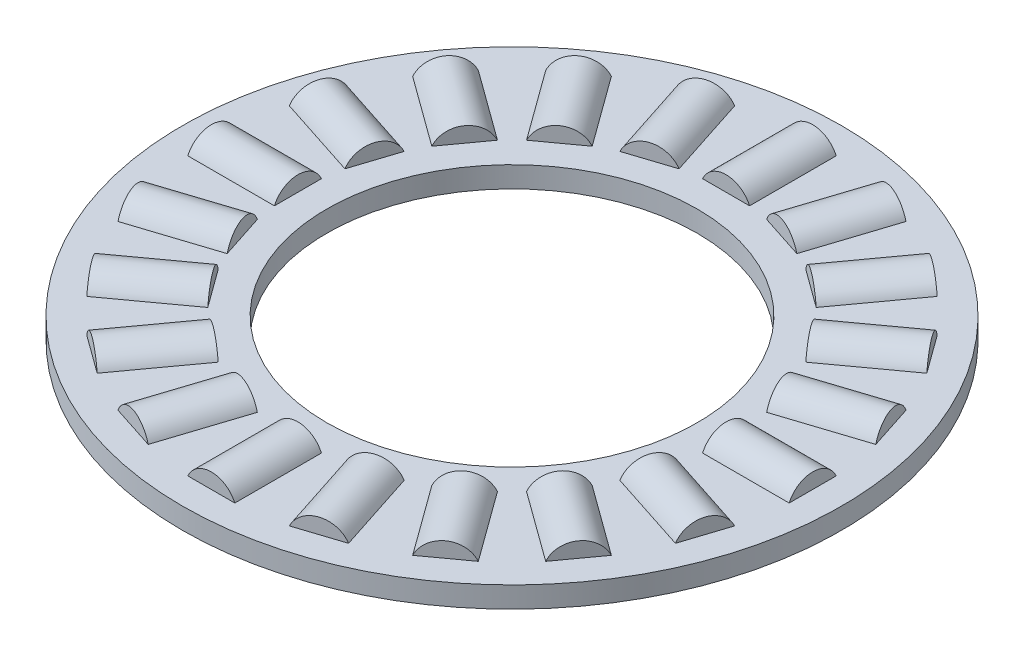
SolidWorks part; units mm, degrees
material "Alloy Steel"
ref_plane "Front Plane" through (0, 0, 0) normal (0, 0, 1) x (1, 0, 0)
ref_plane "Top Plane" through (0, 0, 0) normal (0, 1, 0) x (1, 0, 0)
ref_plane "Right Plane" through (0, 0, 0) normal (1, 0, 0) x (0, 0, -1)
sketch "Sketch1" plane through (0, 0, 0) normal (1, 0, 0) x (0, 0, -1)
  line L0 (-12.7, 0) -> (12.7, 0) construction
  line L1 (0, -0.9922) -> (0, 0.9922) construction
  line L2 (-12.7, 0.405) -> (-7.1374, 0.405)
  line L3 (-12.7, 0.405) -> (-12.7, -0.405)
  line L4 (-12.7, -0.405) -> (-7.1374, -0.405)
  line L5 (-7.1374, 0.405) -> (-7.1374, -0.405)
  line L7 (-9.9187, 0.9922) -> (-9.9187, 0.405) construction
  line L8 (-11.5875, 0.9922) -> (-8.2499, 0.9922) construction
  line L9 (-11.5875, 0.9922) -> (-11.5875, -0.9922) construction
  line L10 (-11.5875, -0.9922) -> (-8.2499, -0.9922) construction
  line L11 (-8.2499, 0.9922) -> (-8.2499, -0.9922) construction
  line L12 (12.7, 0.9922) -> (12.7, -0.9922) construction
  point P16 (-11.5875, 0)
  point P21 (12.7, 0)
  dimension "OD" = 25.4
  dimension "ID" = 14.2748
  dimension "Washer Thickness" = 0.81
  dimension "D1" = 3.3376
  dimension "Thickness" = 1.9844
sketch "Sketch6" plane through (0, 0, 0) normal (0, 1, 0) x (1, 0, 0)
  circle A0 centre (0, 0) radius 12.7 construction
  circle A1 centre (0, 0) radius 7.1374 construction
  circle A2 centre (0, 0) radius 7.1438 construction
  dimension "For Shaft Diameter" = 14.2875
  dimension "OD" = 25.4
  dimension "ID" = 14.2748
sketch "Sketch5" plane through (0, 0, 0) normal (1, 0, 0) x (0, 0, -1)
  line L1 (-12.7, 0.405) -> (-7.1374, 0.405)
  line L2 (-12.7, 0.405) -> (-12.7, -0.405)
  line L3 (-12.7, -0.405) -> (-7.1374, -0.405)
  line L4 (-7.1374, 0.405) -> (-7.1374, -0.405)
revolve "Revolve3" add sketch "Sketch5" angle 360 about L1
sketch "Sketch3" plane through (0, 0, 0) normal (1, 0, 0) x (0, 0, -1)
  line L0 (-11.5875, 0.9922) -> (-11.5875, -0.9922) construction
  line L1 (-11.5875, 0) -> (-8.2499, 0)
  line L2 (-11.5875, 0) -> (-11.5875, 0.9922)
  line L3 (-11.5875, 0.9922) -> (-8.2499, 0.9922)
  line L4 (-8.2499, 0) -> (-8.2499, 0.9922)
revolve "Cut-Revolve1" cut sketch "Sketch3" angle 360 about L1
sketch "Sketch2" plane through (0, 0, 0) normal (1, 0, 0) x (0, 0, -1)
  line L1 (-11.5875, 0) -> (-8.2499, 0)
  line L2 (-11.5875, 0) -> (-11.5875, 0.9922)
  line L3 (-11.5875, 0.9922) -> (-8.2499, 0.9922)
  line L4 (-8.2499, 0) -> (-8.2499, 0.9922)
revolve "Revolve2" add sketch "Sketch2" angle 360 about L1
ref_axis "Axis1" through (0, 0.9922, 0) along (0, -1, 0)
pattern_circular "CirPattern1" count 20 every 18 about axis through (0, 0.9922, 0) along (0, -1, 0) of bodies 187 411
pattern_circular "CirPattern2" count 20 every 18 about axis through (0, 0, 0) along (0, 1, 0) of "Cut-Revolve1"
equation "\"Rollers@CirPattern1\"= \"OD@Sketch1\" * 20"
equation "\"Angle@CirPattern1\" = 360/\"Rollers@CirPattern1\""
equation "\"D1@CirPattern2\" = \"Rollers@CirPattern1\""
equation "\"D2@CirPattern2\" = \"Angle@CirPattern1\""
equation "\"D1@Sketch1\"=((\"OD@Sketch1\"-\"ID@Sketch1\")/2)*.6"
